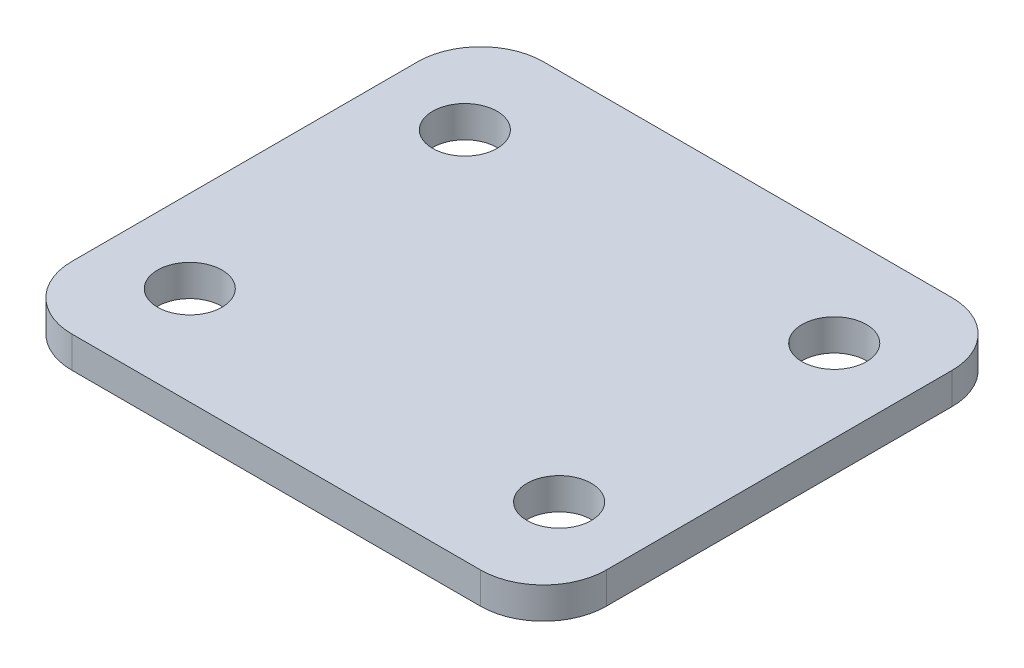
SolidWorks part; units mm, degrees
material "Thornel Mat VMA"
ref_plane "前视基准面" through (0, 0, 0) normal (0, 0, 1) x (1, 0, 0)
ref_plane "上视基准面" through (0, 0, 0) normal (0, 1, 0) x (1, 0, 0)
ref_plane "右视基准面" through (0, 0, 0) normal (1, 0, 0) x (0, 0, -1)
sketch "草图1" plane through (0, 0, 0) normal (0, 1, 0) x (1, 0, 0)
  line L1 (-17, 15) -> (17, 15)
  line L2 (-17, 15) -> (-17, -15)
  line L3 (-17, -15) -> (17, -15)
  line L4 (17, 15) -> (17, -15)
  line L5 (-17, 15) -> (17, -15) construction
  line L6 (-17, -15) -> (17, 15) construction
  line L7 (-11.75, 8.75) -> (11.75, 8.75) construction
  line L8 (-11.75, 8.75) -> (-11.75, -8.75) construction
  line L9 (-11.75, -8.75) -> (11.75, -8.75) construction
  line L10 (11.75, 8.75) -> (11.75, -8.75) construction
  line L11 (-11.75, 8.75) -> (11.75, -8.75) construction
  line L12 (-11.75, -8.75) -> (11.75, 8.75) construction
  circle A0 centre (-11.75, 8.75) radius 2.05
  circle A1 centre (11.75, 8.75) radius 2.05
  circle A2 centre (11.75, -8.75) radius 2.05
  circle A3 centre (-11.75, -8.75) radius 2.05
  point P0 (0, 0)
  point P6 (0, 0)
  dimension "D5" = 4.1
  dimension "D6" = 4.1
  dimension "D7" = 4.1
  dimension "D8" = 4.1
  dimension "D1" = 34
  dimension "D2" = 30
  dimension "D3" = 17.5
  dimension "D4" = 23.5
extrude "凸台-拉伸1" add sketch "草图1" along normal blind 2
fillet "圆角1" radius 4 4 edges at (-17, 1, -15) (17, 1, -15) (17, 1, 15) (-17, 1, 15)
